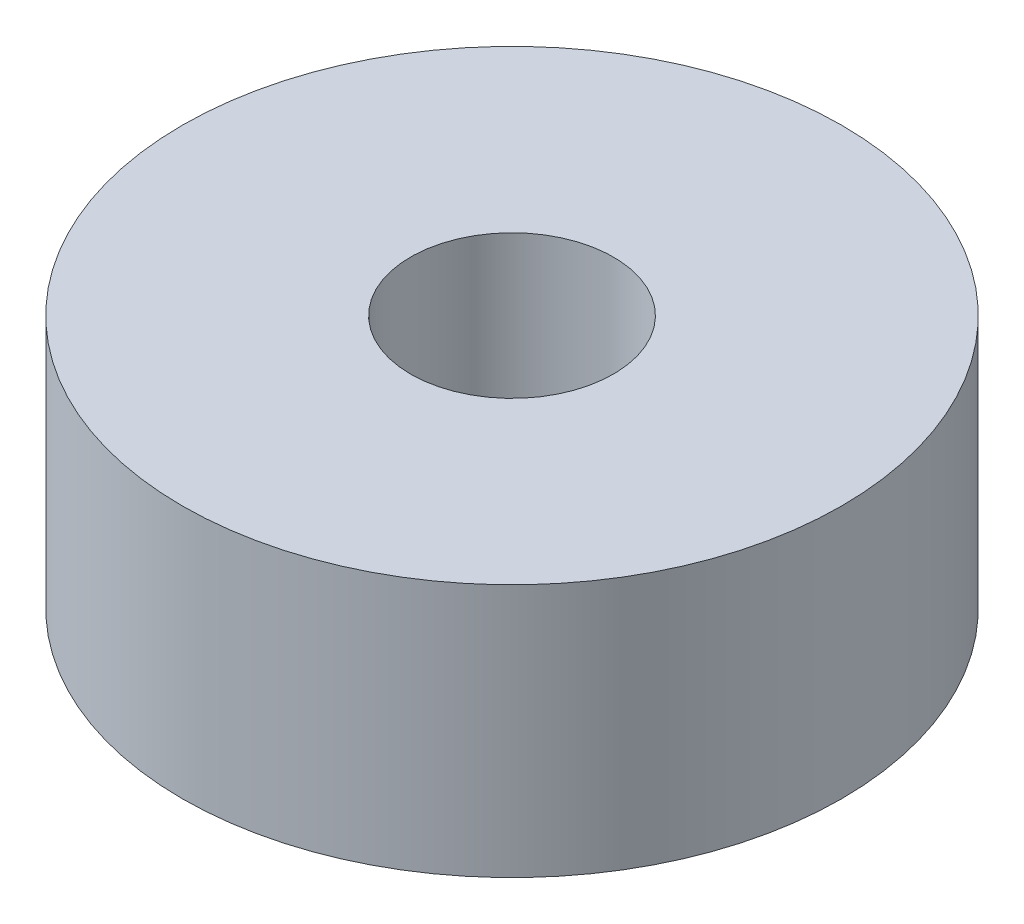
SolidWorks part; units mm, degrees
material "1060 合金"
ref_plane "前视基准面" through (0, 0, 0) normal (0, 0, 1) x (1, 0, 0)
ref_plane "上视基准面" through (0, 0, 0) normal (0, 1, 0) x (1, 0, 0)
ref_plane "右视基准面" through (0, 0, 0) normal (1, 0, 0) x (0, 0, -1)
other "Configuration Table"
sketch "草图1" plane through (0, 0, 0) normal (0, 1, 0) x (1, 0, 0)
  circle A0 centre (0, 0) radius 2
  circle A1 centre (0, 0) radius 6.5
  dimension "D1" = 4
  dimension "D2" = 13
extrude "凸台-拉伸1" add sketch "草图1" along normal blind 5
